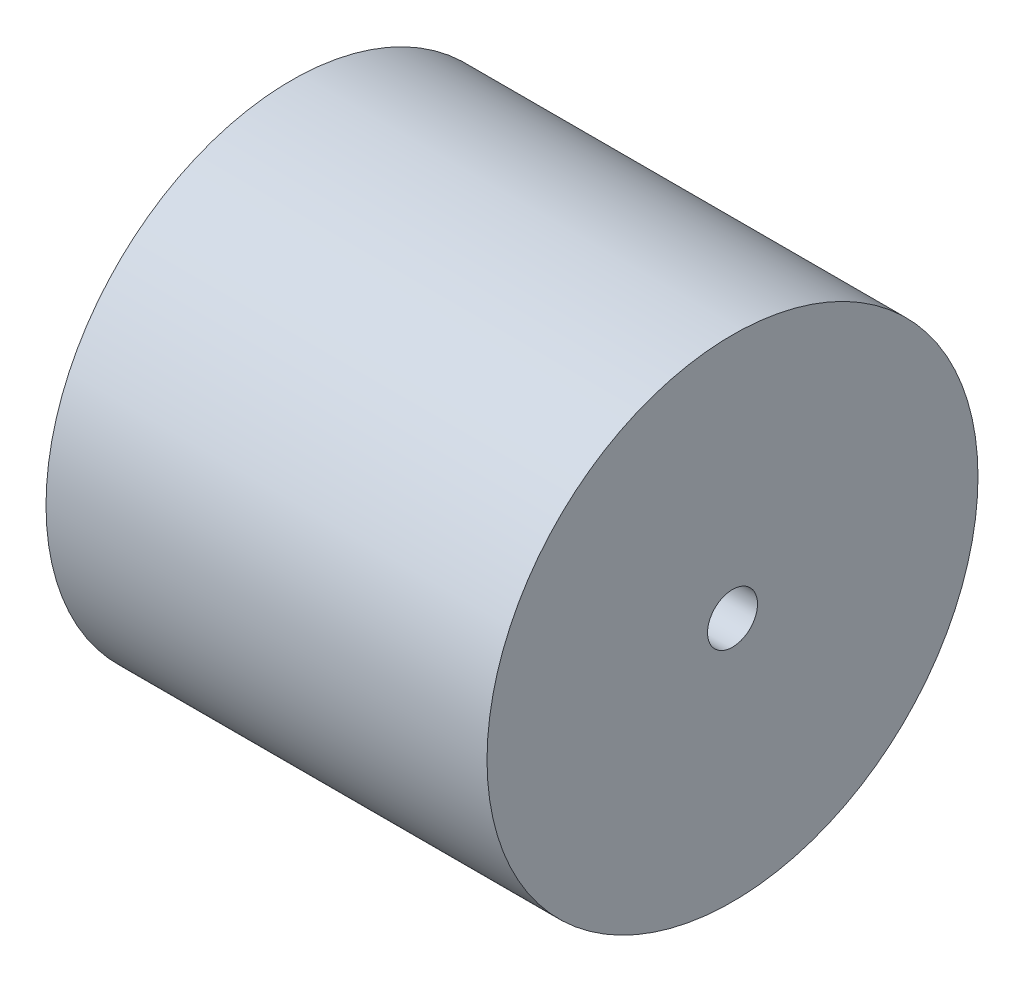
SolidWorks part; units mm, degrees
ref_plane "Front Plane" through (0, 0, 0) normal (1, 0, 0) x (0, 1, 0)
ref_plane "Top Plane" through (0, 0, 0) normal (0, 0, 1) x (0, 1, 0)
ref_plane "Right Plane" through (0, 0, 0) normal (0, 1, 0) x (-1, 0, 0)
sketch "Sketch1" plane through (0, 0, 0) normal (1, 0, 0) x (0, 1, 0)
  circle A0 centre (0, 0) radius 16.7
  dimension "D1" = 33.4
extrude "Boss-Extrude1" add sketch "Sketch1" along normal blind 30
sketch "Sketch2" plane through (30, 0, 0) normal (1, 0, 0) x (0, 1, 0)
  circle A0 centre (0, 0) radius 1.7
  dimension "D1" = 3.4
extrude "Cut-Extrude1" cut sketch "Sketch2" against normal up to next
